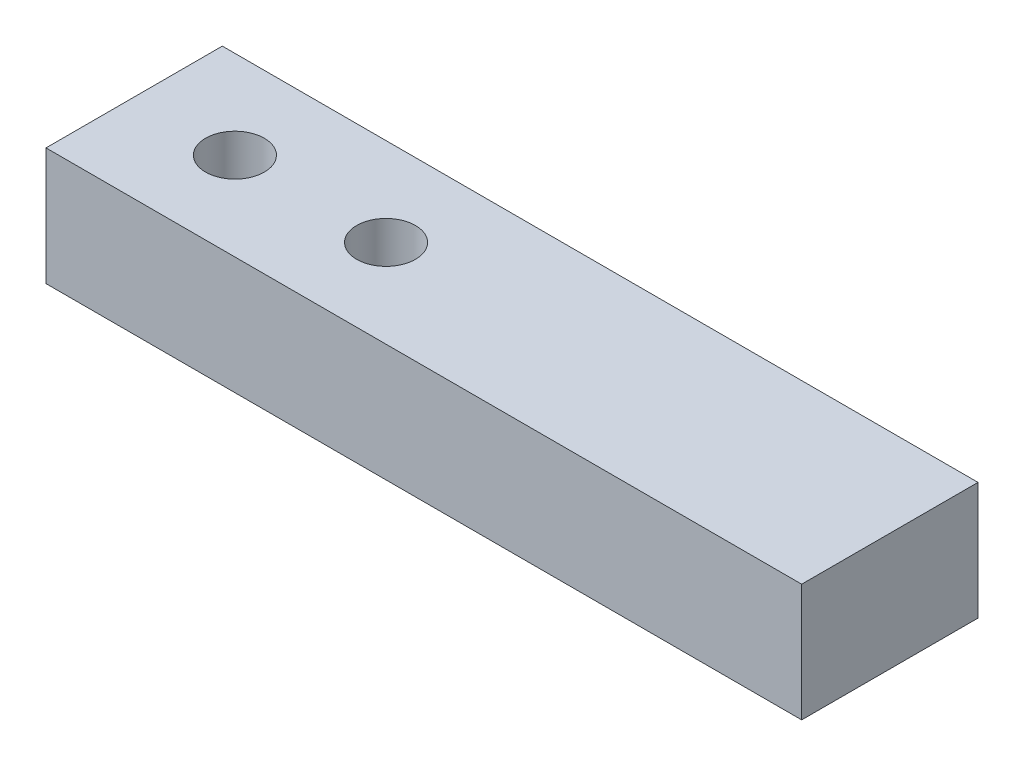
SolidWorks part; units mm, degrees
ref_plane "Front Plane" through (0, 0, 0) normal (0, 0, 1) x (1, 0, 0)
ref_plane "Top Plane" through (0, 0, 0) normal (0, 1, 0) x (1, 0, 0)
ref_plane "Right Plane" through (0, 0, 0) normal (1, 0, 0) x (0, 0, -1)
other "Configuration Table"
sketch "草图1" plane through (0, 0, 0) normal (0, 1, 0) x (1, 0, 0)
  line L0 (-15.4, 0) -> (15.4, 0) construction
  line L1 (-90, -21) -> (90, -21)
  line L2 (-90, -21) -> (-90, 21)
  line L3 (-90, 21) -> (90, 21)
  line L4 (90, -21) -> (90, 21)
  line L5 (-90, -21) -> (90, 21) construction
  line L6 (-90, 21) -> (90, -21) construction
  circle A0 centre (-66, 0) radius 7
  circle A1 centre (-30, 0) radius 7
  point P0 (0, 0)
extrude "凸台-拉伸1" add sketch "草图1" along normal blind 28
